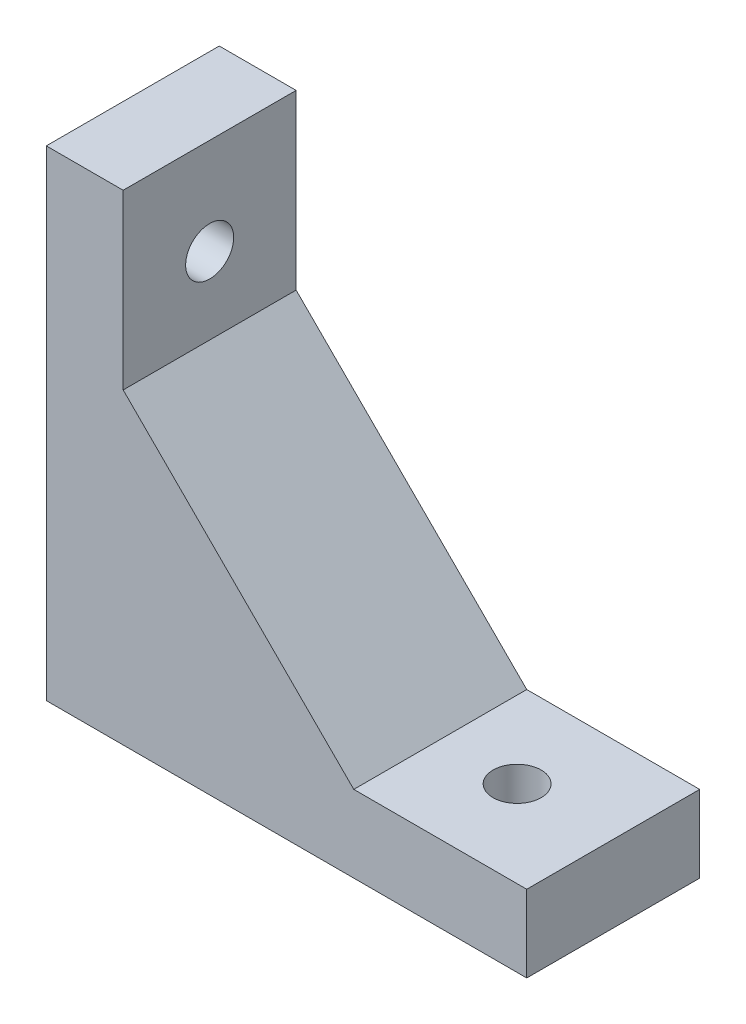
SolidWorks part; units mm, degrees
ref_plane "前视基准面" through (0, 0, 0) normal (0, 0, 1) x (1, 0, 0)
ref_plane "上视基准面" through (0, 0, 0) normal (0, 1, 0) x (1, 0, 0)
ref_plane "右视基准面" through (0, 0, 0) normal (1, 0, 0) x (0, 0, -1)
other "Configuration Table"
sketch "草图1" plane through (0, 0, 0) normal (0, 0, 1) x (1, 0, 0)
  line L0 (32, 8) -> (50, 8)
  line L1 (0, 50) -> (8, 50)
  line L2 (0, 50) -> (0, 0)
  line L4 (8, 50) -> (8, 32)
  line L5 (8, 32) -> (32, 8)
  line L7 (0, 0) -> (50, 0)
  line L10 (50, 0) -> (50, 8)
  dimension "D1" = 8
  dimension "D2" = 8
  dimension "D3" = 50
  dimension "D4" = 50
  dimension "D5" = 45
  dimension "D6" = 18
extrude "凸台-拉伸1" add sketch "草图1" along normal blind 18 contours L1 L4 L5 L0 L10 L7 L2
sketch "草图2" plane through (0, 0, 0) normal (0, -1, 0) x (1, 0, 0)
  line L0 (0, 9) -> (50, 9) construction
  line L4 (0, 0) -> (50, 0)
  line L5 (50, 0) -> (50, 18)
  line L6 (50, 18) -> (0, 18)
  line L7 (0, 18) -> (0, 0)
  line L8 (0, 0) -> (50, 0)
  line L9 (50, 0) -> (50, 18)
  line L10 (50, 18) -> (0, 18)
  line L11 (0, 18) -> (0, 0)
  circle A1 centre (40, 9) radius 2.5
  dimension "D2" = 5
  dimension "D4" = 10
  dimension "D1" = 0
extrude "切除-拉伸1" cut sketch "草图2" against normal through all
sketch "草图3" plane through (0, 0, 0) normal (-1, 0, 0) x (0, 0, 1)
  line L0 (9, 50) -> (9, 0) construction
  line L4 (0, 50) -> (0, 0)
  line L5 (0, 0) -> (18, 0)
  line L6 (18, 0) -> (18, 50)
  line L7 (18, 50) -> (0, 50)
  line L8 (0, 50) -> (0, 0)
  line L9 (0, 0) -> (18, 0)
  line L10 (18, 0) -> (18, 50)
  line L11 (18, 50) -> (0, 50)
  circle A0 centre (9, 40) radius 2.5
  dimension "D2" = 5
  dimension "D4" = 10
  dimension "D1" = 0
extrude "切除-拉伸2" cut sketch "草图3" against normal through all
